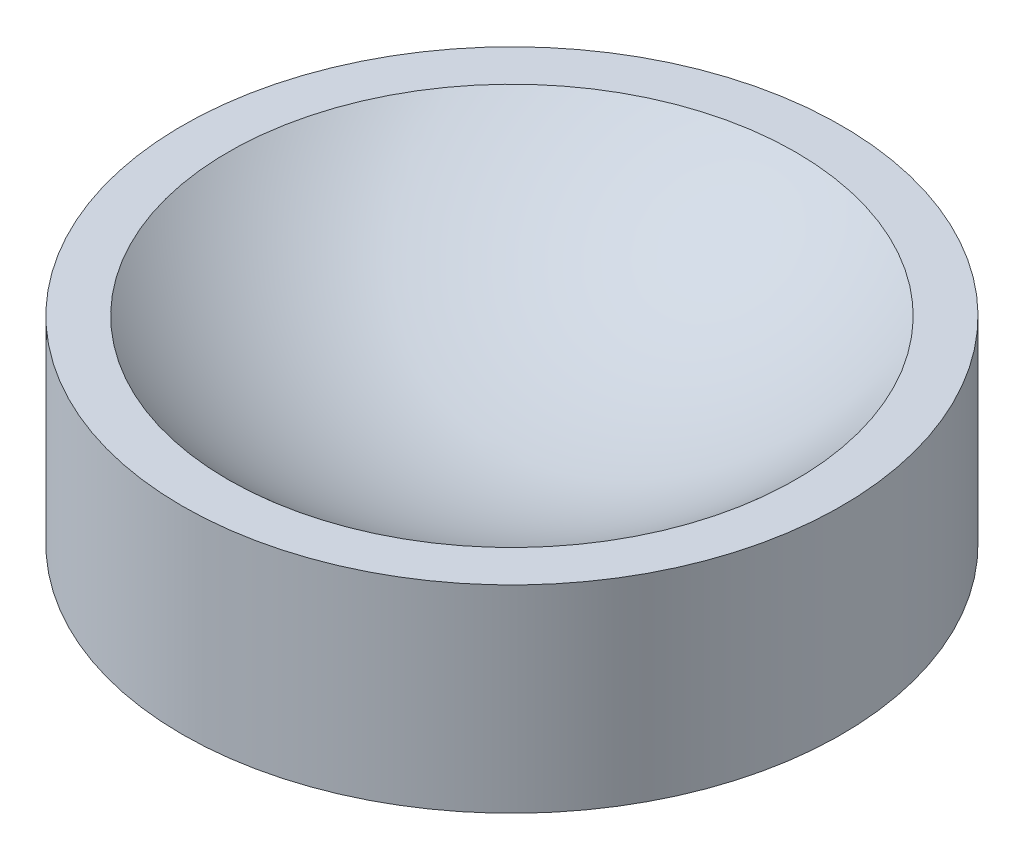
SolidWorks part; units mm, degrees
ref_plane "前视基准面" through (0, 0, 0) normal (0, 0, 1) x (1, 0, 0)
ref_plane "上视基准面" through (0, 0, 0) normal (0, 1, 0) x (1, 0, 0)
ref_plane "右视基准面" through (0, 0, 0) normal (1, 0, 0) x (0, 0, -1)
other "Configuration Table"
sketch "草图1" plane through (0, 0, 0) normal (0, 1, 0) x (1, 0, 0)
  circle A0 centre (0, 0) radius 25
  dimension "D1" = 50
extrude "凸台-拉伸1" add sketch "草图1" along normal blind 15 contours A0
sketch "草图2" plane through (0, 0, 0) normal (0, 0, 1) x (1, 0, 0)
  line L0 (0, 15) -> (0, 38) construction
  line L1 (25, 15) -> (-25, 15) construction
  line L2 (-31.5, 38) -> (0, 38)
  line L3 (0, 38) -> (31.5, 38)
  arc A0 (31.5, 38) -> (-31.5, 38) centre (0, 38) ccw
  point P5 (0, 0)
  point P7 (0, 6.5)
  dimension "D2" = 63
  dimension "D1" = 23
revolve "切除-旋转1" cut sketch "草图2" angle 270 about L3
